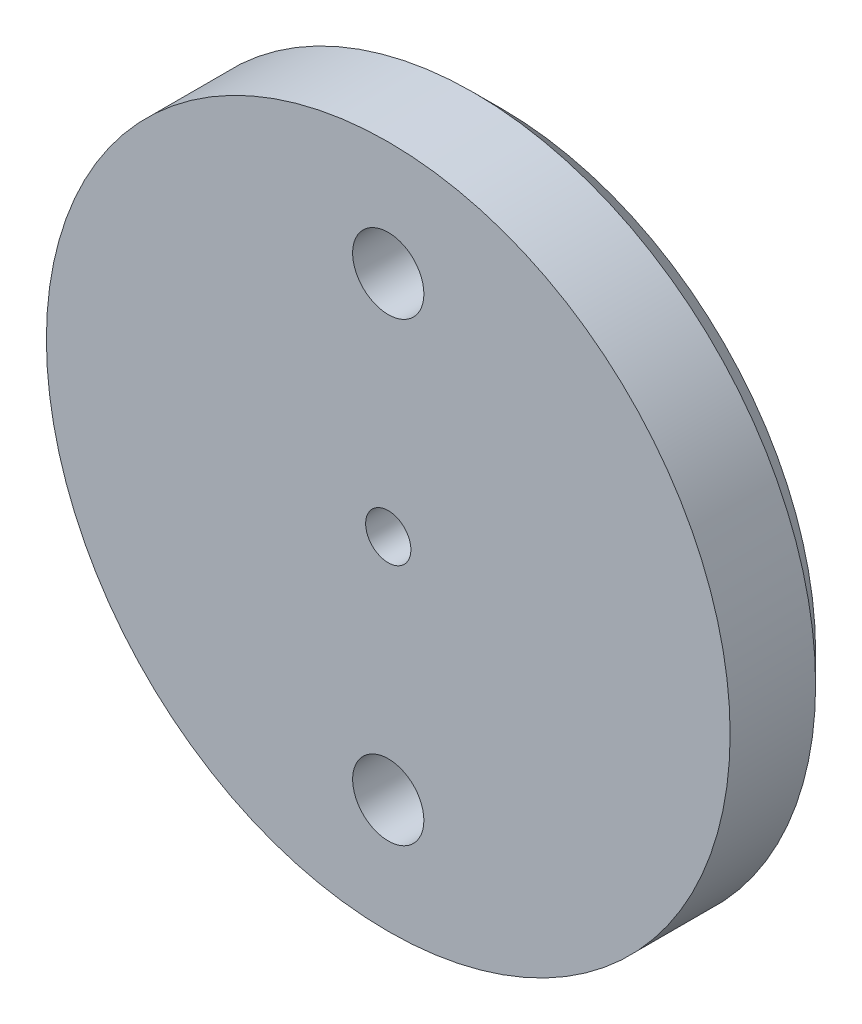
SolidWorks part; units mm, degrees
material "6061-T6 (SS)"
ref_plane "Ground_Plane" through (0, 0, 0) normal (0, 0, 1) x (1, 0, 0)
ref_plane "VehicleCentre_Plane" through (0, 0, 0) normal (0, 1, 0) x (1, 0, 0)
ref_plane "FrontAxle_Plane" through (0, 0, 0) normal (1, 0, 0) x (0, 0, -1)
sketch "Sketch1" plane through (0, 0, 0) normal (0, 1, 0) x (1, 0, 0)
  line L0 (0.7937, 0) -> (12, 0)
  line L1 (12, 0) -> (12, 4)
  line L2 (12, 4) -> (1.5875, 4)
  line L3 (1.5875, 4) -> (1.5875, 8)
  line L4 (1.5875, 8) -> (2, 8)
  line L5 (2, 8) -> (1.4641, 10)
  line L6 (1.4641, 10) -> (0.7937, 10)
  line L7 (0.7937, 10) -> (0.7937, 0)
  line L8 (0, 0) -> (0, 10) construction
  dimension "D1" = 12
  dimension "D2" = 4
  dimension "D3" = 1.5875
  dimension "D4" = 10
  dimension "D5" = 15
  dimension "D6" = 2
  dimension "D7" = 2
  dimension "D8" = 0.7937
revolve "Revolve1" add sketch "Sketch1" angle 360 about L8
hole_wizard "Tap Drill for M3x0.5 Tap1" positions "Sketch4" profile "Sketch5" hole size "M3x0.5" standard "ANSI Metric" end condition through all
sketch "Sketch4" plane through (0, 0, 0) normal (0, 0, 1) x (1, 0, 0)
  point P0 (0, 8)
  point P2 (0, -8)
  dimension "D1" = 8
  dimension "D2" = 16
sketch "Sketch5" plane through (0, 8, 0) normal (1, 0, 0) x (0, -1, 0)
  line L0 (0, 0) -> (0, 10)
  line L1 (0, 10) -> (1.25, 10)
  line L2 (1.25, 10) -> (1.25, 0)
  line L5 (1.25, 0) -> (0, 0)
  line L11 (0, -6.35) -> (0, 107.95) construction
  dimension "Thru Hole Dia." = 2.5
  dimension "Thru Hole Depth" = 10
chamfer "Chamfer1" distance 1 angle 45 1 edges at (12, 0, -4)
fillet "Fillet1" radius 0.5 2 edges at (1.4641, 0, -10) (1.5875, 0, -4)
fillet "Fillet2" radius 0.15 2 edges at (2, 0, -8) (1.5875, 0, -8)
equation "\"D2@Sketch4\"=\"D1@Sketch4\"*2"
